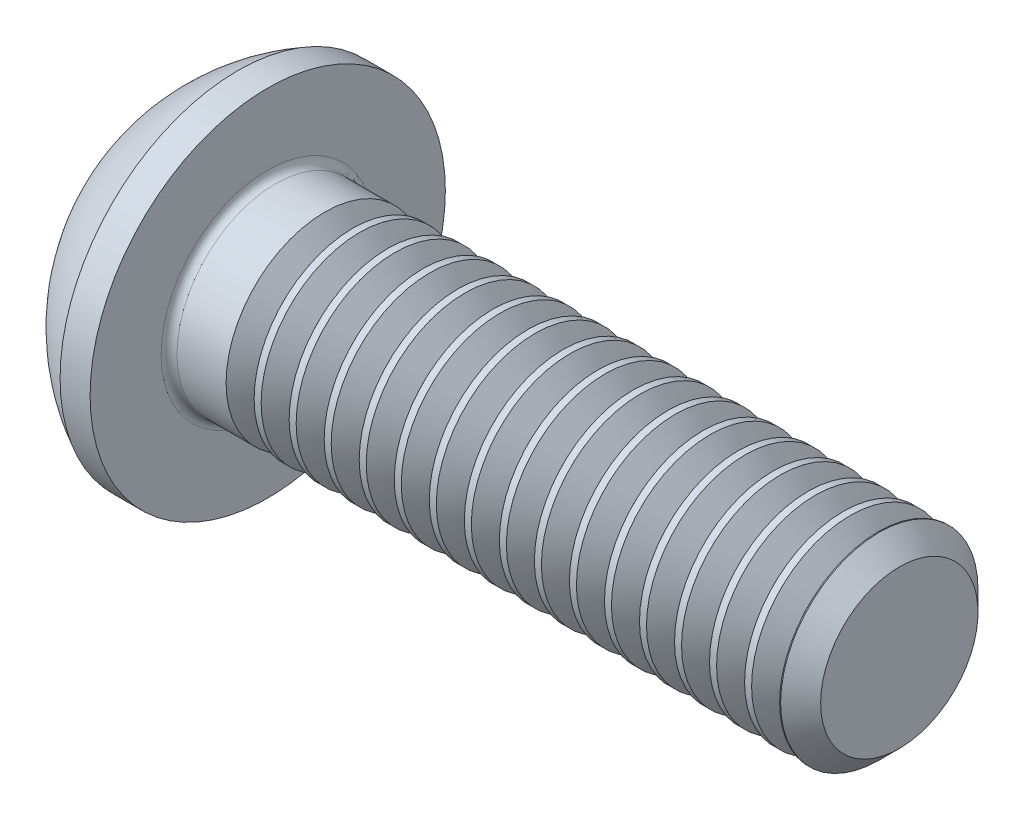
SolidWorks part; units mm, degrees
ref_plane "Plane1" through (0, 0, 0) normal (0, 0, 1) x (1, 0, 0)
ref_plane "Plane2" through (0, 0, 0) normal (0, 1, 0) x (1, 0, 0)
ref_plane "Plane3" through (0, 0, 0) normal (1, 0, 0) x (0, 0, -1)
sketch "BodySke" plane through (0, 0, 0) normal (0, 0, 1) x (1, 0, 0)
  line L0 (9.5, 0) -> (9.5, 0.9965)
  line L1 (9.2465, 1.25) -> (1.5, 1.25)
  line L2 (1.5, 1.25) -> (1.5, 2.25)
  line L3 (1.5, 2.25) -> (1.12, 2.25)
  line L4 (0, 0) -> (101.6, 0) construction
  line L5 (1.5, -2.25) -> (1.12, -2.25) construction
  line L6 (55.6768, -1.25) -> (1.5, -1.25) construction
  line L7 (9.5, 0) -> (0, 0)
  line L8 (0, 1.125) -> (0, -1.125) construction
  line L9 (0, 0) -> (0, 1.125)
  line L10 (9.5, 0.9965) -> (9.2465, 1.25)
  line L11 (9.5, -0.9965) -> (9.2465, -1.25) construction
  line L12 (1.95, 9.525) -> (1.95, -1.25) construction
  line L13 (1.5, 9.525) -> (1.5, -1.25) construction
  arc A1 (0, 1.125) -> (1.12, 2.25) centre (2.255, 0) cw
  dimension "Diameter" = 2.5
  dimension "Length" = 8
  dimension "Head_dia" = 4.5
  dimension "D1" = 2.25
  dimension "Head_ht" = 1.5
  dimension "Head_side_ht" = 0.38
  dimension "Minor_dia" = 1.993
  dimension "Body_ch_ang" = 45
  dimension "Advance" = 0.45
  dimension "Thread_nom" = 8
revolve "BaseBody" add sketch "BodySke" angle 360 about L4
cosmetic thread "ThreadCosmetic" [suppressed] parameters "Thread_length"=7.1, "Thread_minor"=1.993
fillet "Fillet1" radius 0.1 1 edges at (1.5, 0, 1.25)
sketch "Sketch2" plane through (0, 0, 0) normal (0, 0, 1) x (1, 0, 0)
  line L0 (0, 0.75) -> (0.8, 0.75)
  line L1 (0.8, 0.75) -> (1.233, 0)
  line L3 (1.233, 0) -> (0, 0)
  line L4 (0, 0) -> (0, 0.75)
  line L5 (0, -0.75) -> (0.8, -0.75) construction
  line L6 (0, 0) -> (47.625, 0) construction
  dimension "D2" = 60
  dimension "PreBroach_depth" = 0.8
  dimension "PreBroach_dia" = 1.5
revolve "PreBroach" cut sketch "Sketch2" angle 360 about L6
sketch "Sketch3" plane through (0, 0, 0) normal (1, 0, 0) x (0, 0, -1)
  line L0 (-0.75, -0.433) -> (-0.75, 0.433)
  line L1 (-0.75, 0.433) -> (0, 0.866)
  line L2 (0, 0.866) -> (0.75, 0.433)
  line L3 (0.75, 0.433) -> (0.75, -0.433)
  line L4 (0.75, -0.433) -> (0, -0.866)
  line L5 (0, -0.866) -> (-0.75, -0.433)
  dimension "Hex_size" = 1.5
  dimension "D3" = 1.5
  dimension "D1" = 0.75
  dimension "D2" = 0.75
extrude "Hex" cut sketch "Sketch3" along normal blind 0.8
sketch "ThdSchSke" plane through (0, 0, 0) normal (0, 0, 1) x (1, 0, 0)
  line L0 (2.4, -0.9965) -> (2.2225, -1.25)
  line L1 (2.4, -0.9965) -> (2.5775, -1.25)
  line L2 (2.5775, -1.25) -> (2.5775, -1.5625)
  line L3 (-3.175, 0) -> (5.1513, 0) construction
  line L5 (2.5775, -1.5625) -> (2.2225, -1.5625)
  line L6 (2.2225, -1.5625) -> (2.2225, -1.25)
  dimension "Diameter" = 2.5
  dimension "Thread_minor" = 1.993
  dimension "SideAngle" = 55
  dimension "VeeAngle" = 70
  dimension "Overcut" = 3.125
  dimension "Start" = 2.4
revolve "ThreadSchematic" cut sketch "ThdSchSke" angle 360 about L3
pattern_linear "ThdSchPat" count 16 spacing 0.4438 along (1, 0, 0) of "ThreadSchematic"
equation "\"D1@BodySke\" = \"Head_dia@BodySke\" * .5"
equation "\"Thread_minor@ThreadCosmetic\" = \"Minor_dia@BodySke\""
equation "\"D1@Sketch3\" = \"Hex_size@Sketch3\" / 2"
equation "\"D2@Sketch3\" = \"D1@Sketch3\""
equation "\"D3@Sketch3\" = \"Hex_size@Sketch3\""
equation "\"Thread_length@ThreadCosmetic\" = ((sgn( (\"Length@BodySke\" - \"Advance@BodySke\" * 2.0) - \"Thread_nom@BodySke\" )-1)*( (\"Length@BodySke\" - \"Advance@BodySke\" * 2.0) - \"Thread_nom@BodySke\" ))/-2+ \"Thread_nom@BodySke\""
equation "\"Thread_minor@ThdSchSke\" = \"Minor_dia@BodySke\""
equation "\"Diameter@ThdSchSke\" = \"Diameter@BodySke\""
equation "\"Overcut@ThdSchSke\" = \"Diameter@BodySke\" * 1.25"
equation "\"Start@ThdSchSke\" = \"Head_ht@BodySke\" + \"Length@BodySke\" - \"Thread_length@ThreadCosmetic\"  '---Non-countersunk---"
equation "\"Num_threads@ThdSchPat\" = int( \"Thread_length@ThreadCosmetic\" / \"Advance@BodySke\" + 0.999 )  + 1"
equation "\"Advance@ThdSchPat\" = \"Thread_length@ThreadCosmetic\" /  (\"Num_threads@ThdSchPat\" - 1) 'relax it"
equation "\"Num_threads@ThdSchPat\" = \"Num_threads@ThdSchPat\" - sgn( \"Num_threads@ThdSchPat\" - 1) '---chamfered tips only---"
